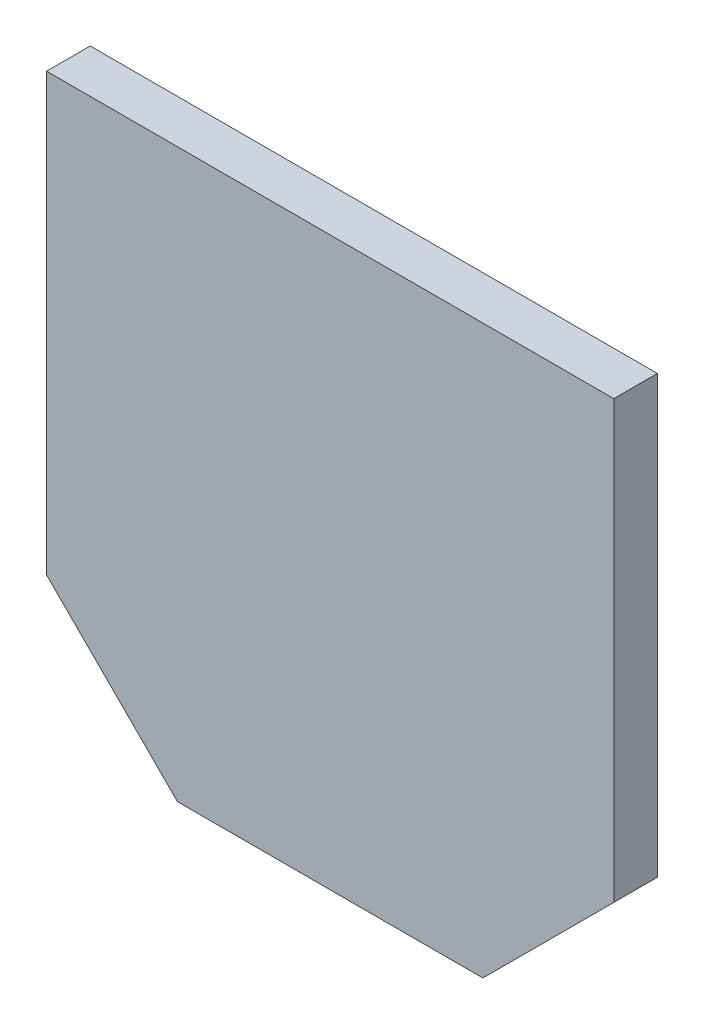
SolidWorks part; units mm, degrees
ref_plane "Front Plane" through (0, 0, 0) normal (0, 0, 1) x (1, 0, 0)
ref_plane "Top Plane" through (0, 0, 0) normal (0, 1, 0) x (1, 0, 0)
ref_plane "Right Plane" through (0, 0, 0) normal (1, 0, 0) x (0, 0, -1)
sketch "Sketch1" plane through (0, 0, 0) normal (0, 0, 1) x (1, 0, 0)
  line L0 (0, 0) -> (0, 130)
  line L1 (0, 130) -> (130, 130)
  line L2 (130, 130) -> (130, 0)
  line L3 (130, 0) -> (0, 0)
  dimension "D1" = 130
  dimension "D2" = 130
extrude "Boss-Extrude2" add sketch "Sketch1" along normal blind 10
chamfer "Chamfer1" distance 30 angle 45 2 edges at (130, 0, 5) (0, 0, 5)
